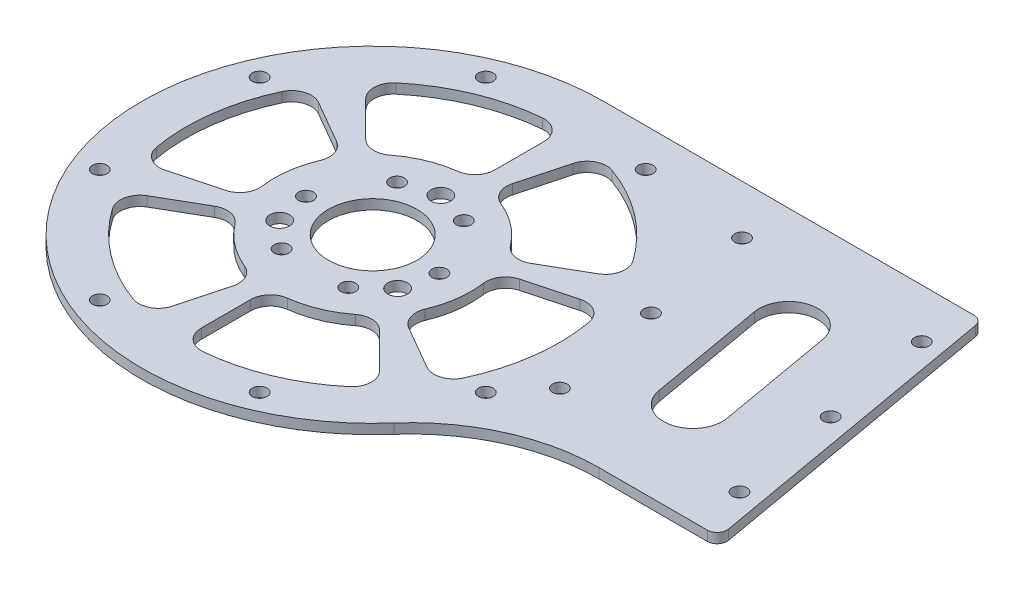
SolidWorks part; units mm, degrees
material "Hexcel AS4C (3000 丝)"
ref_plane "前视基准面" through (0, 0, 0) normal (0, 0, 1) x (1, 0, 0)
ref_plane "上视基准面" through (0, 0, 0) normal (0, 1, 0) x (1, 0, 0)
ref_plane "右视基准面" through (0, 0, 0) normal (1, 0, 0) x (0, 0, -1)
sketch "草图1" plane through (0, 0, 0) normal (0, 1, 0) x (1, 0, 0)
  line L0 (-247.6136, -26.9029) -> (538.3864, -26.9029) construction
  line L1 (0, 47) -> (75.3218, 47)
  line L2 (86.0777, -18) -> (64.0777, -18)
  line L3 (77.2914, 45.3473) -> (88.0474, -15.6527)
  line L5 (-16.264, 39.2649) -> (-39.2649, 16.264) construction
  line L6 (-39.2649, 16.264) -> (-39.2649, -16.264) construction
  line L7 (-39.2649, -16.264) -> (-16.264, -39.2649) construction
  line L8 (-16.264, -39.2649) -> (16.264, -39.2649) construction
  line L9 (16.264, -39.2649) -> (39.2649, -16.264) construction
  line L10 (39.2649, -16.264) -> (39.2649, 16.264) construction
  line L11 (39.2649, 16.264) -> (16.264, 39.2649) construction
  line L12 (16.264, 39.2649) -> (-16.264, 39.2649) construction
  line L13 (6.7839, -11.75) -> (13.5677, 0) construction
  line L14 (13.5677, 0) -> (6.7839, 11.75) construction
  line L15 (6.7839, 11.75) -> (-6.7839, 11.75) construction
  line L16 (-6.7839, 11.75) -> (-13.5677, 0) construction
  line L17 (-13.5677, 0) -> (-6.7839, -11.75) construction
  line L18 (-6.7839, -11.75) -> (6.7839, -11.75) construction
  line L19 (0, 13.8564) -> (-12, 6.9282) construction
  line L20 (-12, 6.9282) -> (-12, -6.9282) construction
  line L21 (-12, -6.9282) -> (0, -13.8564) construction
  line L22 (0, -13.8564) -> (12, -6.9282) construction
  line L23 (12, -6.9282) -> (12, 6.9282) construction
  line L24 (12, 6.9282) -> (0, 13.8564) construction
  circle A0 centre (0, 0) radius 47 construction
  arc A1 (64.0777, -18) -> (35.3098, -31.0197) centre (64.0777, -56.2924) ccw
  arc A2 (75.3218, 47) -> (77.2914, 45.3473) centre (75.3218, 45) cw
  arc A3 (86.0777, -18) -> (88.0474, -15.6527) centre (86.0777, -16) ccw
  arc A4 (0, 47) -> (35.3098, -31.0197) centre (0, 0) ccw
  circle A5 centre (0, 0) radius 42.5 construction
  circle A6 centre (-16.264, 39.2649) radius 1.5
  circle A7 centre (16.264, 39.2649) radius 1.5
  circle A8 centre (39.2649, 16.264) radius 1.5 construction
  circle A9 centre (39.2649, -16.264) radius 1.5
  circle A10 centre (16.264, -39.2649) radius 1.5
  circle A11 centre (-16.264, -39.2649) radius 1.5
  circle A12 centre (-39.2649, -16.264) radius 1.5
  circle A13 centre (-39.2649, 16.264) radius 1.5
  circle A14 centre (0, 0) radius 9
  circle A15 centre (0, 0) radius 11.75 construction
  circle A16 centre (-6.7839, 11.75) radius 1.5
  circle A17 centre (6.7839, 11.75) radius 1.5
  circle A18 centre (13.5677, 0) radius 1.5
  circle A19 centre (6.7839, -11.75) radius 1.5
  circle A20 centre (-6.7839, -11.75) radius 1.5
  circle A21 centre (-13.5677, 0) radius 1.5
  circle A22 centre (0, 0) radius 12 construction
  circle A23 centre (0, 13.8564) radius 2
  circle A24 centre (-12, -6.9282) radius 2
  circle A25 centre (12, -6.9282) radius 2
  point P13 (77, 47)
  dimension "D1" = 94
  dimension "D5" = 2
  dimension "D7" = 85
  dimension "D8" = 3
  dimension "D9" = 18
  dimension "D11" = 3
  dimension "D13" = 4
  dimension "D2" = 80
  dimension "D3" = 77
  dimension "D4" = 65
  dimension "D6" = 22
  dimension "D10" = 23.5
  dimension "D12" = 24
extrude "凸台-拉伸1" add sketch "草图1" along normal blind 2
sketch "草图2" plane through (0, 2, 0) normal (0, 1, 0) x (1, 0, 0)
  line L0 (68.8766, 47) -> (116.6298, -223.8221) construction
  line L1 (68.8766, 47) -> (41.302, 42.1379) construction
  line L2 (116.6298, -223.8221) -> (89.0552, -228.6843) construction
  line L3 (41.302, 42.1379) -> (89.0552, -228.6843) construction
  line L4 (68.8766, 47) -> (89.0552, -228.6843) construction
  line L5 (116.6298, -223.8221) -> (41.302, 42.1379) construction
  line L6 (88.0474, -15.6527) -> (77.2914, 45.3473) construction
  line L7 (75.3218, 47) -> (0, 47) construction
  line L8 (74.7016, 37) -> (82.6363, -8) construction
  line L9 (64.0777, -18) -> (86.0777, -18) construction
  line L10 (78.9659, -90.8421) -> (67.6998, -26.9489) construction
  line L11 (38.1462, 37) -> (46.0809, -8) construction
  line L12 (78.6689, 14.5) -> (42.1136, 14.5) construction
  line L13 (58.3075, 26.3177) -> (62.475, 2.6823) construction
  line L14 (64.2163, 27.3596) -> (68.3839, 3.7242)
  line L15 (52.3986, 25.2758) -> (56.5662, 1.6404)
  circle A0 centre (74.7016, 37) radius 1.5
  circle A1 centre (78.6689, 14.5) radius 1.5
  circle A2 centre (82.6363, -8) radius 1.5
  circle A3 centre (38.1462, 37) radius 1.5
  circle A4 centre (46.0809, -8) radius 1.5
  circle A5 centre (42.1136, 14.5) radius 1.5
  arc A6 (64.2163, 27.3596) -> (52.3986, 25.2758) centre (58.3075, 26.3177) ccw
  arc A7 (56.5662, 1.6404) -> (68.3839, 3.7242) centre (62.475, 2.6823) ccw
  point P1 (78.9659, -90.8421)
  point P27 (60.3912, 14.5)
  dimension "D7" = 3
  dimension "D1" = 28
  dimension "D2" = 8
  dimension "D3" = 275
  dimension "D4" = 10
  dimension "D5" = 10
  dimension "D6" = 4
  dimension "D8" = 4
  dimension "D9" = 10
  dimension "D10" = 10
  dimension "D11" = 12
  dimension "D12" = 24
extrude "切除-拉伸1" cut sketch "草图2" against normal through all both and the other way through all
sketch "草图3" plane through (0, 0, 0) normal (0, -1, 0) x (1, 0, 0)
  line L2 (28.83, 17.7997) -> (20.1216, 12.7719)
  line L3 (22.7416, -7.1289) -> (32.4546, -9.7315)
  line L4 (28.83, 17.7997) -> (20.1216, 12.7719)
  line L5 (22.7416, -7.1289) -> (32.4546, -9.7315)
  line L6 (29.83, -16.0677) -> (21.1216, -11.0399)
  line L7 (5.197, -23.2592) -> (7.7996, -32.9722)
  line L8 (29.83, -16.0677) -> (21.1216, -11.0399)
  line L9 (5.197, -23.2592) -> (7.7996, -32.9722)
  line L10 (-29.83, 16.0677) -> (-21.1216, 11.0399)
  line L11 (-5.197, 23.2592) -> (-7.7996, 32.9722)
  line L12 (-29.83, 16.0677) -> (-21.1216, 11.0399)
  line L13 (-5.197, 23.2592) -> (-7.7996, 32.9722)
  line L14 (1, -33.8674) -> (1, -23.8118)
  line L15 (-17.5446, -16.1304) -> (-24.655, -23.2408)
  line L16 (1, -33.8674) -> (1, -23.8118)
  line L17 (-17.5446, -16.1304) -> (-24.655, -23.2408)
  line L18 (-28.83, -17.7997) -> (-20.1216, -12.7719)
  line L19 (-22.7416, 7.1289) -> (-32.4546, 9.7315)
  line L20 (-28.83, -17.7997) -> (-20.1216, -12.7719)
  line L21 (-22.7416, 7.1289) -> (-32.4546, 9.7315)
  line L22 (-1, 33.8674) -> (-1, 23.8118)
  line L23 (17.5446, 16.1304) -> (24.655, 23.2408)
  line L24 (-1, 33.8674) -> (-1, 23.8118)
  line L25 (17.5446, 16.1304) -> (24.655, 23.2408)
  circle A1 centre (12, 6.9282) radius 3
  circle A2 centre (12, 6.9282) radius 3
  circle A3 centre (-12, 6.9282) radius 3
  circle A4 centre (-12, 6.9282) radius 3
  circle A5 centre (0, -13.8564) radius 3
  arc A6 (20.1216, 12.7719) -> (18.4347, 7.7565) centre (22.1216, 9.3078) ccw
  arc A7 (34.4571, 16.0222) -> (28.83, 17.7997) centre (30.83, 14.3356) ccw
  arc A8 (37.4298, -6.5581) -> (34.4571, 16.0222) centre (0, 0) ccw
  arc A9 (32.4546, -9.7315) -> (37.4298, -6.5581) centre (33.4898, -5.8677) ccw
  arc A10 (19.814, -2.721) -> (22.7416, -7.1289) centre (23.7769, -3.2652) ccw
  arc A11 (19.814, -2.721) -> (18.4347, 7.7565) centre (0, 0) ccw
  arc A12 (20.1216, 12.7719) -> (18.4347, 7.7565) centre (22.1216, 9.3078) ccw
  arc A13 (34.4571, 16.0222) -> (28.83, 17.7997) centre (30.83, 14.3356) ccw
  arc A14 (37.4298, -6.5581) -> (34.4571, 16.0222) centre (0, 0) ccw
  arc A15 (32.4546, -9.7315) -> (37.4298, -6.5581) centre (33.4898, -5.8677) ccw
  arc A16 (19.814, -2.721) -> (22.7416, -7.1289) centre (23.7769, -3.2652) ccw
  arc A17 (19.814, -2.721) -> (18.4347, 7.7565) centre (0, 0) ccw
  arc A18 (21.1216, -11.0399) -> (15.9347, -12.0866) centre (19.1216, -14.504) ccw
  arc A19 (31.1041, -21.8296) -> (29.83, -16.0677) centre (27.83, -19.5318) ccw
  arc A20 (13.0355, -35.6942) -> (31.1041, -21.8296) centre (0, 0) ccw
  arc A21 (7.7996, -32.9722) -> (13.0355, -35.6942) centre (11.6633, -31.9369) ccw
  arc A22 (7.5506, -18.5199) -> (5.197, -23.2592) centre (9.0607, -22.2239) ccw
  arc A23 (7.5506, -18.5199) -> (15.9347, -12.0866) centre (0, 0) ccw
  arc A24 (21.1216, -11.0399) -> (15.9347, -12.0866) centre (19.1216, -14.504) ccw
  arc A25 (31.1041, -21.8296) -> (29.83, -16.0677) centre (27.83, -19.5318) ccw
  arc A26 (13.0355, -35.6942) -> (31.1041, -21.8296) centre (0, 0) ccw
  arc A27 (7.7996, -32.9722) -> (13.0355, -35.6942) centre (11.6633, -31.9369) ccw
  arc A28 (7.5506, -18.5199) -> (5.197, -23.2592) centre (9.0607, -22.2239) ccw
  arc A29 (7.5506, -18.5199) -> (15.9347, -12.0866) centre (0, 0) ccw
  arc A30 (-21.1216, 11.0399) -> (-15.9347, 12.0866) centre (-19.1216, 14.504) ccw
  arc A31 (-31.1041, 21.8296) -> (-29.83, 16.0677) centre (-27.83, 19.5318) ccw
  arc A32 (-13.0355, 35.6942) -> (-31.1041, 21.8296) centre (0, 0) ccw
  arc A33 (-7.7996, 32.9722) -> (-13.0355, 35.6942) centre (-11.6633, 31.9369) ccw
  arc A34 (-7.5506, 18.5199) -> (-5.197, 23.2592) centre (-9.0607, 22.2239) ccw
  arc A35 (-7.5506, 18.5199) -> (-15.9347, 12.0866) centre (0, 0) ccw
  arc A36 (-21.1216, 11.0399) -> (-15.9347, 12.0866) centre (-19.1216, 14.504) ccw
  arc A37 (-31.1041, 21.8296) -> (-29.83, 16.0677) centre (-27.83, 19.5318) ccw
  arc A38 (-13.0355, 35.6942) -> (-31.1041, 21.8296) centre (0, 0) ccw
  arc A39 (-7.7996, 32.9722) -> (-13.0355, 35.6942) centre (-11.6633, 31.9369) ccw
  arc A40 (-7.5506, 18.5199) -> (-5.197, 23.2592) centre (-9.0607, 22.2239) ccw
  arc A41 (-7.5506, 18.5199) -> (-15.9347, 12.0866) centre (0, 0) ccw
  arc A42 (1, -23.8118) -> (-2.5, -19.8431) centre (-3, -23.8118) ccw
  arc A43 (-3.3529, -37.8518) -> (1, -33.8674) centre (-3, -33.8674) ccw
  arc A44 (-24.3944, -29.1361) -> (-3.3529, -37.8518) centre (0, 0) ccw
  arc A45 (-24.655, -23.2408) -> (-24.3944, -29.1361) centre (-21.8265, -26.0692) ccw
  arc A46 (-12.2634, -15.799) -> (-17.5446, -16.1304) centre (-14.7161, -18.9588) ccw
  arc A47 (-12.2634, -15.799) -> (-2.5, -19.8431) centre (0, 0) ccw
  arc A48 (1, -23.8118) -> (-2.5, -19.8431) centre (-3, -23.8118) ccw
  arc A49 (-3.3529, -37.8518) -> (1, -33.8674) centre (-3, -33.8674) ccw
  arc A50 (-24.3944, -29.1361) -> (-3.3529, -37.8518) centre (0, 0) ccw
  arc A51 (-24.655, -23.2408) -> (-24.3944, -29.1361) centre (-21.8265, -26.0692) ccw
  arc A52 (-12.2634, -15.799) -> (-17.5446, -16.1304) centre (-14.7161, -18.9588) ccw
  arc A53 (-12.2634, -15.799) -> (-2.5, -19.8431) centre (0, 0) ccw
  arc A54 (-20.1216, -12.7719) -> (-18.4347, -7.7565) centre (-22.1216, -9.3078) ccw
  arc A55 (-34.4571, -16.0222) -> (-28.83, -17.7997) centre (-30.83, -14.3356) ccw
  arc A56 (-37.4298, 6.5581) -> (-34.4571, -16.0222) centre (0, 0) ccw
  arc A57 (-32.4546, 9.7315) -> (-37.4298, 6.5581) centre (-33.4898, 5.8677) ccw
  arc A58 (-19.814, 2.721) -> (-22.7416, 7.1289) centre (-23.7769, 3.2652) ccw
  arc A59 (-19.814, 2.721) -> (-18.4347, -7.7565) centre (0, 0) ccw
  arc A60 (-20.1216, -12.7719) -> (-18.4347, -7.7565) centre (-22.1216, -9.3078) ccw
  arc A61 (-34.4571, -16.0222) -> (-28.83, -17.7997) centre (-30.83, -14.3356) ccw
  arc A62 (-37.4298, 6.5581) -> (-34.4571, -16.0222) centre (0, 0) ccw
  arc A63 (-32.4546, 9.7315) -> (-37.4298, 6.5581) centre (-33.4898, 5.8677) ccw
  arc A64 (-19.814, 2.721) -> (-22.7416, 7.1289) centre (-23.7769, 3.2652) ccw
  arc A65 (-19.814, 2.721) -> (-18.4347, -7.7565) centre (0, 0) ccw
  circle A66 centre (0, -13.8564) radius 3
  circle A67 centre (-13.5677, 0) radius 2.5
  circle A68 centre (-13.5677, 0) radius 2.5
  circle A69 centre (-6.7839, 11.75) radius 2.5
  circle A70 centre (-6.7839, 11.75) radius 2.5
  circle A71 centre (6.7839, 11.75) radius 2.5
  circle A72 centre (6.7839, 11.75) radius 2.5
  circle A73 centre (13.5677, 0) radius 2.5
  circle A74 centre (13.5677, 0) radius 2.5
  circle A75 centre (-6.7839, -11.75) radius 2.5
  circle A76 centre (-6.7839, -11.75) radius 2.5
  circle A77 centre (6.7839, -11.75) radius 2.5
  circle A78 centre (6.7839, -11.75) radius 2.5
  circle A79 centre (0, 0) radius 10
  circle A80 centre (0, 0) radius 10
  circle A81 centre (-39.2649, -16.264) radius 2.5
  circle A82 centre (-39.2649, -16.264) radius 2.5
  circle A83 centre (-39.2649, 16.264) radius 2.5
  circle A84 centre (-39.2649, 16.264) radius 2.5
  circle A85 centre (-16.264, 39.2649) radius 2.5
  circle A86 centre (-16.264, 39.2649) radius 2.5
  circle A87 centre (16.264, 39.2649) radius 2.5
  circle A88 centre (16.264, 39.2649) radius 2.5
  circle A89 centre (39.2649, 16.264) radius 2.5
  circle A90 centre (39.2649, 16.264) radius 2.5
  circle A91 centre (16.264, -39.2649) radius 2.5
  circle A92 centre (16.264, -39.2649) radius 2.5
  circle A93 centre (-16.264, -39.2649) radius 2.5
  circle A94 centre (-16.264, -39.2649) radius 2.5
  arc A100 (-1, 23.8118) -> (2.5, 19.8431) centre (3, 23.8118) ccw
  arc A101 (3.3529, 37.8518) -> (-1, 33.8674) centre (3, 33.8674) ccw
  arc A102 (24.3944, 29.1361) -> (3.3529, 37.8518) centre (0, 0) ccw
  arc A103 (24.655, 23.2408) -> (24.3944, 29.1361) centre (21.8265, 26.0692) ccw
  arc A104 (12.2634, 15.799) -> (17.5446, 16.1304) centre (14.7161, 18.9588) ccw
  arc A105 (12.2634, 15.799) -> (2.5, 19.8431) centre (0, 0) ccw
  arc A106 (-1, 23.8118) -> (2.5, 19.8431) centre (3, 23.8118) ccw
  arc A107 (3.3529, 37.8518) -> (-1, 33.8674) centre (3, 33.8674) ccw
  arc A108 (24.3944, 29.1361) -> (3.3529, 37.8518) centre (0, 0) ccw
  arc A109 (24.655, 23.2408) -> (24.3944, 29.1361) centre (21.8265, 26.0692) ccw
  arc A110 (12.2634, 15.799) -> (17.5446, 16.1304) centre (14.7161, 18.9588) ccw
  arc A111 (12.2634, 15.799) -> (2.5, 19.8431) centre (0, 0) ccw
  dimension "D1" = 0
  dimension "D2" = 0
  dimension "D3" = 0
  dimension "D4" = 0
  dimension "D5" = 0
  dimension "D6" = 0
  dimension "D7" = 0
  dimension "D8" = 0
  dimension "D9" = 0
  dimension "D10" = 0
  dimension "D11" = 0
  dimension "D12" = 0
  dimension "D13" = 0
  dimension "D14" = 0
  dimension "D15" = 0
  dimension "D16" = 0
  dimension "D17" = 0
  dimension "D18" = 0
  dimension "D19" = 0
  dimension "D20" = 0
  dimension "D21" = 0
  dimension "D22" = 0
  dimension "D23" = 0
extrude "切除-拉伸2" cut sketch "草图3" against normal through all both and the other way through all contours A29 A28 L9 A27 A26 A25 L8 A24 | A53 A52 L17 A51 A50 A49 L16 A48 | A65 A64 L21 A63 A62 A61 L20 A60 | A41 A40 L13 A39 A38 A37 L12 A36 | A111 A110 L25 A109 A108 A107 L24 A106 | A17 A16 L5 A15 A14 A13 L4 A12
